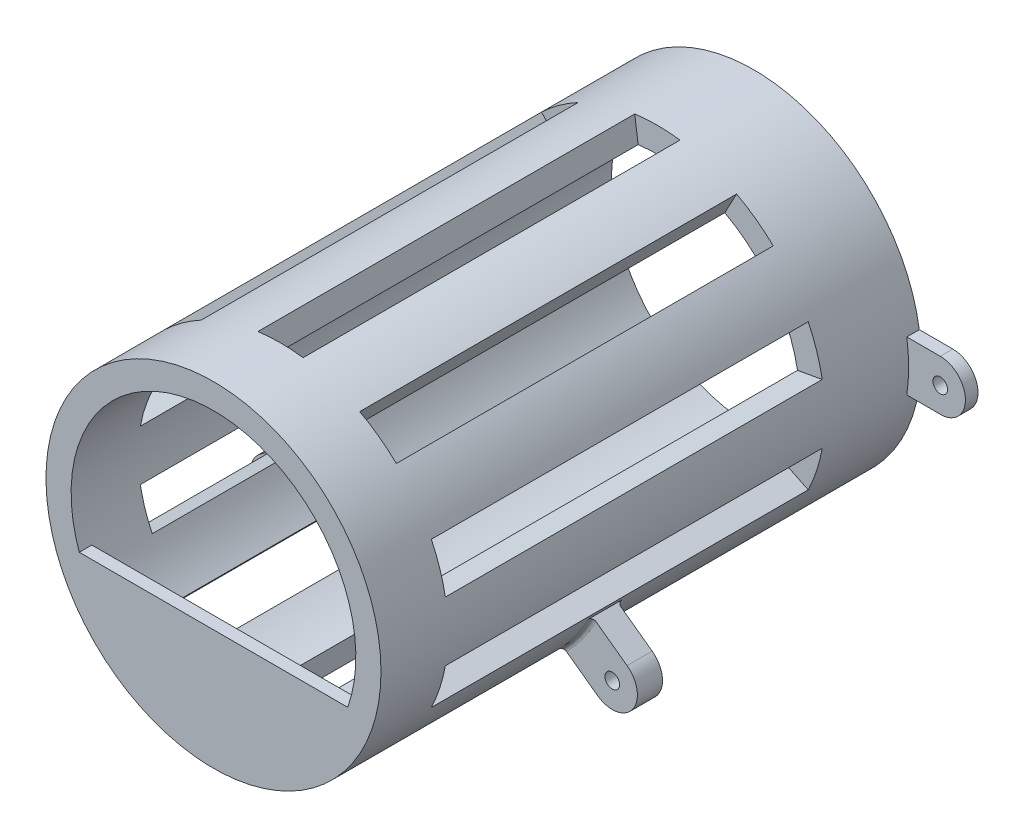
SolidWorks part; units mm, degrees
ref_plane "Front Plane" through (0, 0, 0) normal (0, 0, 1) x (1, 0, 0)
ref_plane "Top Plane" through (0, 0, 0) normal (0, 1, 0) x (1, 0, 0)
ref_plane "Right Plane" through (0, 0, 0) normal (1, 0, 0) x (0, 0, -1)
sketch "Sketch2" plane through (0, 0, 0) normal (0, 0, 1) x (1, 0, 0)
  circle A0 centre (0, 0) radius 40
  circle A1 centre (0, 0) radius 34
  dimension "D1" = 68
  dimension "D2" = 80
extrude "Boss-Extrude1" add sketch "Sketch2" along normal blind 129
sketch "Sketch3" plane through (0, 0, 129) normal (0, 0, 1) x (1, 0, 0)
  line L0 (-38.3593, -11.3387) -> (38.3593, -11.3387)
  circle A0 centre (0, 0) radius 40 construction
  arc A1 (-38.3593, -11.3387) -> (38.3593, -11.3387) centre (0, 0) ccw
extrude "Boss-Extrude2" add sketch "Sketch3" against normal blind 3
ref_plane "Plane1" through (0, 0, 68) normal (0, 0, 1) x (1, 0, 0)
sketch "Sketch4" plane through (0, 0, 68) normal (0, 0, 1) x (1, 0, 0)
  line L0 (0, 0) -> (0, 31.7526) construction
  line L1 (0, 0) -> (-54.7013, -39.7428) construction
  line L2 (-35.5225, -18.3889) -> (-43.7568, -24.3748)
  line L4 (-28.4697, -28.0976) -> (-36.5599, -33.9754)
  line L6 (28.4697, -28.0976) -> (36.5599, -33.9754)
  line L7 (35.5225, -18.3889) -> (43.7568, -24.3748)
  circle A0 centre (0, 0) radius 40 construction
  arc A1 (-43.7568, -24.3748) -> (-36.5599, -33.9754) centre (-40.2301, -29.2289) ccw
  arc A2 (-35.5225, -18.3889) -> (-28.4697, -28.0976) centre (0, 0) ccw
  circle A3 centre (-40.2301, -29.2289) radius 1.75
  circle A4 centre (40.2301, -29.2289) radius 1.75
  arc A5 (35.5225, -18.3889) -> (28.4697, -28.0976) centre (0, 0) cw
  arc A6 (43.7568, -24.3748) -> (36.5599, -33.9754) centre (40.2301, -29.2289) cw
  dimension "D3" = 10
  dimension "D4" = 3.5
  dimension "D1" = 54
  dimension "D5" = 6
  dimension "D6" = 12
extrude "Boss-Extrude3" add sketch "Sketch4" along normal blind 6
fillet "Fillet1" radius 1 4 edges at (-32.3623, -23.5092, 68) (-32.3623, -23.5092, 74) (32.3623, -23.5092, 68) (32.3623, -23.5092, 74)
sketch "Sketch5" plane through (0, 0, 0) normal (0, 0, -1) x (-1, 0, 0)
  line L0 (-40, 0) -> (40, 0) construction
  line L1 (0, 0) -> (0, 17.8653) construction
  line L2 (-39.5474, 6) -> (-47.5474, 6)
  line L4 (-39.5474, -6) -> (-48.1512, -6)
  line L6 (39.5474, -6) -> (48.1512, -6)
  line L7 (39.5474, 6) -> (47.5474, 6)
  circle A0 centre (0, 0) radius 40 construction
  arc A1 (-47.5474, 6) -> (-48.1512, -6) centre (-47.5474, -0.0152) ccw
  circle A2 centre (-47.5474, -0.0152) radius 1.75
  arc A3 (-39.5474, 6) -> (-39.5474, -6) centre (0, 0) ccw
  arc A4 (39.5474, 6) -> (39.5474, -6) centre (0, 0) cw
  circle A5 centre (47.5474, -0.0152) radius 1.75
  arc A6 (47.5474, 6) -> (48.1512, -6) centre (47.5474, -0.0152) cw
  dimension "D3" = 8
  dimension "D4" = 80
  dimension "D1" = 6
  dimension "D2" = 6
extrude "Boss-Extrude4" add sketch "Sketch5" against normal blind 3
sketch "Sketch6" plane through (0, 0, 68) normal (0, 0, 1) x (1, 0, 0)
  line L0 (-5.4054, 39.6331) -> (-4.5946, 33.6881)
  line L1 (5.4054, 39.6331) -> (4.5946, 33.6881)
  line L2 (18.9227, 35.2411) -> (16.0843, 29.9549)
  line L3 (0, 0) -> (0, 40) construction
  line L4 (27.6688, 28.8866) -> (23.5185, 24.5536)
  line L5 (36.0229, 17.3881) -> (30.6195, 14.7799)
  line L6 (39.3637, 7.1065) -> (33.4591, 6.0405)
  line L7 (39.3637, -7.1065) -> (33.4591, -6.0405)
  line L8 (36.0229, -17.3881) -> (30.6195, -14.7799)
  line L9 (27.6688, -28.8866) -> (23.5185, -24.5536)
  line L10 (18.9227, -35.2411) -> (16.0843, -29.9549)
  line L11 (5.4054, -39.6331) -> (4.5946, -33.6881)
  line L12 (-5.4054, -39.6331) -> (-4.5946, -33.6881)
  line L13 (-18.9227, -35.2411) -> (-16.0843, -29.9549)
  line L14 (-27.6688, -28.8866) -> (-23.5185, -24.5536)
  line L15 (-36.0229, -17.3881) -> (-30.6195, -14.7799)
  line L16 (-39.3637, -7.1065) -> (-33.4591, -6.0405)
  line L17 (-39.3637, 7.1065) -> (-33.4591, 6.0405)
  line L18 (-36.0229, 17.3881) -> (-30.6195, 14.7799)
  line L19 (-27.6688, 28.8866) -> (-23.5185, 24.5536)
  line L20 (-18.9227, 35.2411) -> (-16.0843, 29.9549)
  arc A0 (-18.9227, 35.2411) -> (-27.6688, 28.8866) centre (0, 0) ccw
  arc A1 (-16.0843, 29.9549) -> (-23.5185, 24.5536) centre (0, 0) ccw
  arc A2 (-30.6195, 14.7799) -> (-33.4591, 6.0405) centre (0, 0) ccw
  arc A3 (-36.0229, 17.3881) -> (-39.3637, 7.1065) centre (0, 0) ccw
  arc A4 (-33.4591, -6.0405) -> (-30.6195, -14.7799) centre (0, 0) ccw
  arc A5 (-39.3637, -7.1065) -> (-36.0229, -17.3881) centre (0, 0) ccw
  arc A6 (-23.5185, -24.5536) -> (-16.0843, -29.9549) centre (0, 0) ccw
  arc A7 (-27.6688, -28.8866) -> (-18.9227, -35.2411) centre (0, 0) ccw
  arc A8 (-4.5946, -33.6881) -> (4.5946, -33.6881) centre (0, 0) ccw
  arc A9 (-5.4054, -39.6331) -> (5.4054, -39.6331) centre (0, 0) ccw
  arc A10 (16.0843, -29.9549) -> (23.5185, -24.5536) centre (0, 0) ccw
  arc A11 (18.9227, -35.2411) -> (27.6688, -28.8866) centre (0, 0) ccw
  arc A12 (30.6195, -14.7799) -> (33.4591, -6.0405) centre (0, 0) ccw
  arc A13 (36.0229, -17.3881) -> (39.3637, -7.1065) centre (0, 0) ccw
  arc A14 (33.4591, 6.0405) -> (30.6195, 14.7799) centre (0, 0) ccw
  arc A15 (39.3637, 7.1065) -> (36.0229, 17.3881) centre (0, 0) ccw
  arc A16 (23.5185, 24.5536) -> (16.0843, 29.9549) centre (0, 0) ccw
  arc A17 (27.6688, 28.8866) -> (18.9227, 35.2411) centre (0, 0) ccw
  arc A18 (4.5946, 33.6881) -> (-4.5946, 33.6881) centre (0, 0) ccw
  arc A19 (5.4054, 39.6331) -> (-5.4054, 39.6331) centre (0, 0) ccw
  point P6 (-5, 36.6606)
  point P49 (0, 0)
  dimension "D1" = 10
  dimension "D3" = 80
  dimension "D4" = 68
  dimension "D2" = 5
extrude "Cut-Extrude1" cut sketch "Sketch6" against normal mid plane 90
